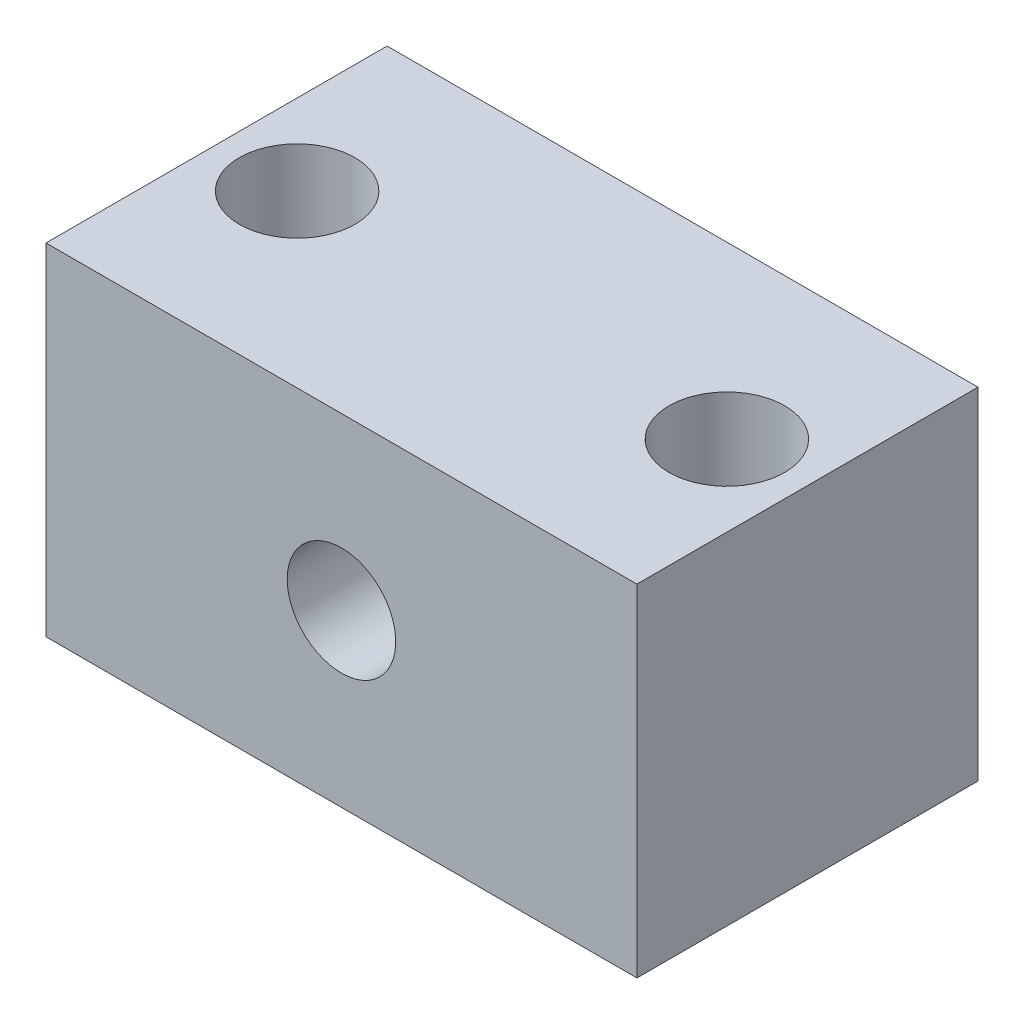
SolidWorks part; units mm, degrees
material "6061-T6 (SS)"
ref_plane "Front Plane" through (0, 0, 0) normal (0, 0, 1) x (1, 0, 0)
ref_plane "Top Plane" through (0, 0, 0) normal (0, 1, 0) x (1, 0, 0)
ref_plane "Right Plane" through (0, 0, 0) normal (1, 0, 0) x (0, 0, -1)
sketch "Sketch1" plane through (0, 0, 0) normal (0, 1, 0) x (1, 0, 0)
  line L0 (22, 0.35) -> (22, 12.35) construction
  line L1 (0, 0) -> (22, 0)
  line L2 (0, 0) -> (0, 12.7)
  line L3 (0, 12.7) -> (22, 12.7)
  line L4 (22, 0) -> (22, 12.7)
  dimension "D1" = 12.7
extrude "Boss-Extrude1" add sketch "Sketch1" along normal mid plane 12.7
hole_wizard "#18 (0.1695) Diameter Hole1" positions "3DSketch1" profile "Sketch3" hole size "#18" standard "ANSI Inch" end condition through all
sketch3d "3DSketch1"
  line L0 (0, 6.35, -6.35) -> (22, 6.35, -6.35) construction
  line L1 (0, 6.35, -12.7) -> (0, 6.35, 0) construction
  line L2 (22, 6.35, 0) -> (22, 6.35, -12.7) construction
  point P0 (3, 6.35, -6.35)
  dimension "D1" = 3
sketch "Sketch3" plane through (3, 6.35, -6.35) normal (1, 0, 0) x (0, 0, 1)
  line L0 (0, 0) -> (0, 12.7)
  line L1 (0, 12.7) -> (2.1526, 12.7)
  line L2 (2.1526, 12.7) -> (2.1526, 0)
  line L5 (2.1526, 0) -> (0, 0)
  line L11 (0, -6.35) -> (0, 107.95) construction
  dimension "Thru Hole Dia." = 4.3053
  dimension "Thru Hole Depth" = 12.7
hole_wizard "#18 (0.1695) Diameter Hole2" positions "3DSketch2" profile "Sketch4" hole size "#18" standard "ANSI Inch" end condition through all
sketch3d "3DSketch2"
  line L0 (3, 6.35, -6.35) -> (19, 6.35, -6.35) construction
  line L1 (3, -6.35, -6.35) -> (3, 6.35, -6.35) construction
  line L4 (0, 6.35, 0) -> (22, 6.35, 0) construction
  point P0 (19, 6.35, -6.35)
  dimension "D1" = 16
sketch "Sketch4" plane through (19, 6.35, -6.35) normal (1, 0, 0) x (0, 0, 1)
  line L0 (0, 0) -> (0, 12.7)
  line L1 (0, 12.7) -> (2.1526, 12.7)
  line L2 (2.1526, 12.7) -> (2.1526, 0)
  line L5 (2.1526, 0) -> (0, 0)
  line L11 (0, -6.35) -> (0, 107.95) construction
  dimension "Thru Hole Dia." = 4.3053
  dimension "Thru Hole Depth" = 12.7
hole_wizard "#10-32 Tapped Hole1" positions "3DSketch3" profile "Sketch5" tap size "#10-32" standard "ANSI Inch" end condition through all
sketch3d "3DSketch3"
  line L0 (0, 0, -12.7) -> (22, 0, -12.7) construction
  line L1 (0, 6.35, -12.7) -> (0, -6.35, -12.7) construction
  line L2 (22, 6.35, -12.7) -> (22, -6.35, -12.7) construction
  point P0 (11, 0, -12.7)
sketch "Sketch5" plane through (11, 0, -12.7) normal (1, 0, 0) x (0, 1, 0)
  line L0 (0, 0) -> (0, 12.7)
  line L1 (0, 12.7) -> (2.0193, 12.7)
  line L2 (2.0193, 12.7) -> (2.0193, 0)
  line L5 (2.0193, 0) -> (0, 0)
  line L11 (0, -6.35) -> (0, 107.95) construction
  dimension "Thru Tap Drill Dia." = 4.0386
  dimension "Thru Tap Drill Depth" = 12.7
cosmetic thread "Hole Thread2" parameters "D2"=4.826
equation "\"D1@3DSketch2\"=16mm"
